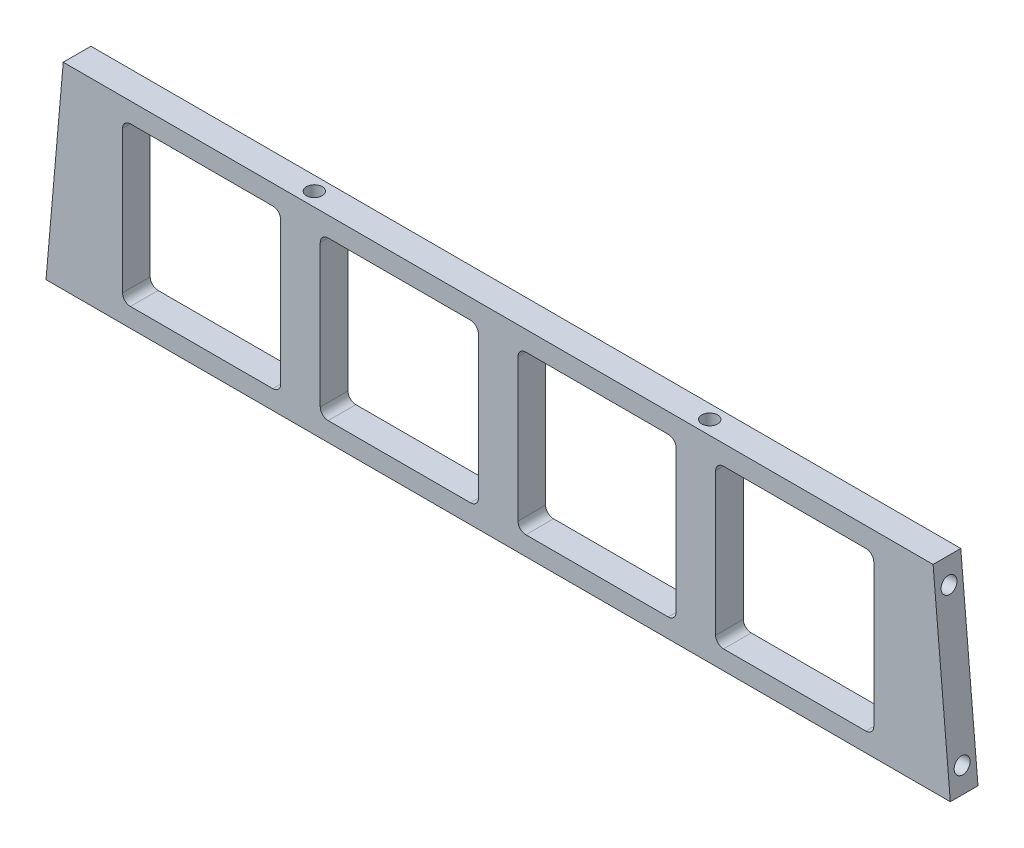
SolidWorks part; units mm, degrees
ref_plane "前视基准面" through (0, 0, 0) normal (0, 0, 1) x (1, 0, 0)
ref_plane "上视基准面" through (0, 0, 0) normal (0, 1, 0) x (1, 0, 0)
ref_plane "右视基准面" through (0, 0, 0) normal (1, 0, 0) x (0, 0, -1)
sketch "草图1" plane through (0, 0, 0) normal (0, 0, 1) x (1, 0, 0)
  line L0 (0, 0) -> (220, 0)
  line L1 (220, 0) -> (224.3578, -49.8097)
  line L2 (0, 0) -> (-4.3578, -49.8097)
  line L3 (-4.3578, -49.8097) -> (224.3578, -49.8097)
  dimension "D1" = 220
  dimension "D2" = 95
  dimension "D3" = 95
  dimension "D4" = 50
extrude "凸台-拉伸1" add sketch "草图1" along normal blind 7
sketch "草图2" plane through (0, 0, 0) normal (-0.9962, 0.0872, 0) x (0, 0, 1)
  line L0 (7, -50) -> (0, -50) construction
  line L1 (0, 0) -> (0, -50) construction
  line L2 (7, 0) -> (0, 0) construction
  circle A0 centre (3.5, -6) radius 2
  circle A3 centre (3.5, -44) radius 2
  dimension "D1" = 6
  dimension "D7" = 4
  dimension "D8" = 4
  dimension "D4" = 6
  dimension "D9" = 3.5
extrude "切除-拉伸1" cut sketch "草图2" against normal blind 10
ref_plane "基准面1" through (110, 0, 0) normal (1, 0, 0) x (0, 0, -1)
mirror "镜向1" about plane through (110, 0, 0) normal (1, 0, 0) of "切除-拉伸1"
sketch "草图3" plane through (0, 0, 0) normal (0, 0, -1) x (-1, 0, 0)
  line L1 (-205, -5) -> (-165, -5)
  line L2 (-205, -5) -> (-205, -45)
  line L3 (-205, -45) -> (-165, -45)
  line L4 (-115, -5) -> (-115, -45)
  line L5 (-15, -5) -> (-55, -5)
  line L6 (-15, -5) -> (-15, -45)
  line L7 (-15, -45) -> (-55, -45)
  line L8 (-105, -5) -> (-105, -45)
  line L10 (-220, 0) -> (0, 0) construction
  line L11 (-165, -5) -> (-165, -45)
  line L12 (-155, -5) -> (-155, -45)
  line L13 (-55, -5) -> (-55, -45)
  line L14 (-65, -5) -> (-65, -45)
  line L15 (-155, -5) -> (-115, -5)
  line L16 (-155, -45) -> (-115, -45)
  line L17 (-65, -5) -> (-105, -5)
  line L18 (-65, -45) -> (-105, -45)
  point P19 (-65, -25)
  dimension "D1" = 40
  dimension "D2" = 90
  dimension "D3" = 90
  dimension "D4" = 10
  dimension "D5" = 15
  dimension "D6" = 40
  dimension "D7" = 5
  dimension "D8" = 5
  dimension "D9" = 10
  dimension "D10" = 10
  dimension "D11" = 40
  dimension "D12" = 40
extrude "切除-拉伸2" cut sketch "草图3" against normal blind 7
fillet "圆角1" radius 2 8 edges at (115, -45, 3.5) (155, -45, 3.5) (115, -5, 3.5) (155, -5, 3.5) (165, -5, 3.5) (165, -45, 3.5) (205, -45, 3.5) (205, -5, 3.5)
fillet "圆角2" radius 2 8 edges at (15, -5, 3.5) (15, -45, 3.5) (55, -5, 3.5) (55, -45, 3.5) (65, -45, 3.5) (65, -5, 3.5) (105, -45, 3.5) (105, -5, 3.5)
sketch "草图4" plane through (0, 0, 0) normal (0, 1, 0) x (1, 0, 0)
  line L0 (220, 0) -> (0, 0) construction
  line L1 (55, 0) -> (55, -7) construction
  line L3 (165, -7) -> (165, 0) construction
  circle A0 centre (60, -3.5) radius 2
  circle A1 centre (160, -3.5) radius 2
  dimension "D1" = 4
  dimension "D2" = 4
  dimension "D6" = 5
  dimension "D3" = 3.5
  dimension "D4" = 3.5
  dimension "D5" = 5
extrude "切除-拉伸3" cut sketch "草图4" against normal blind 90
